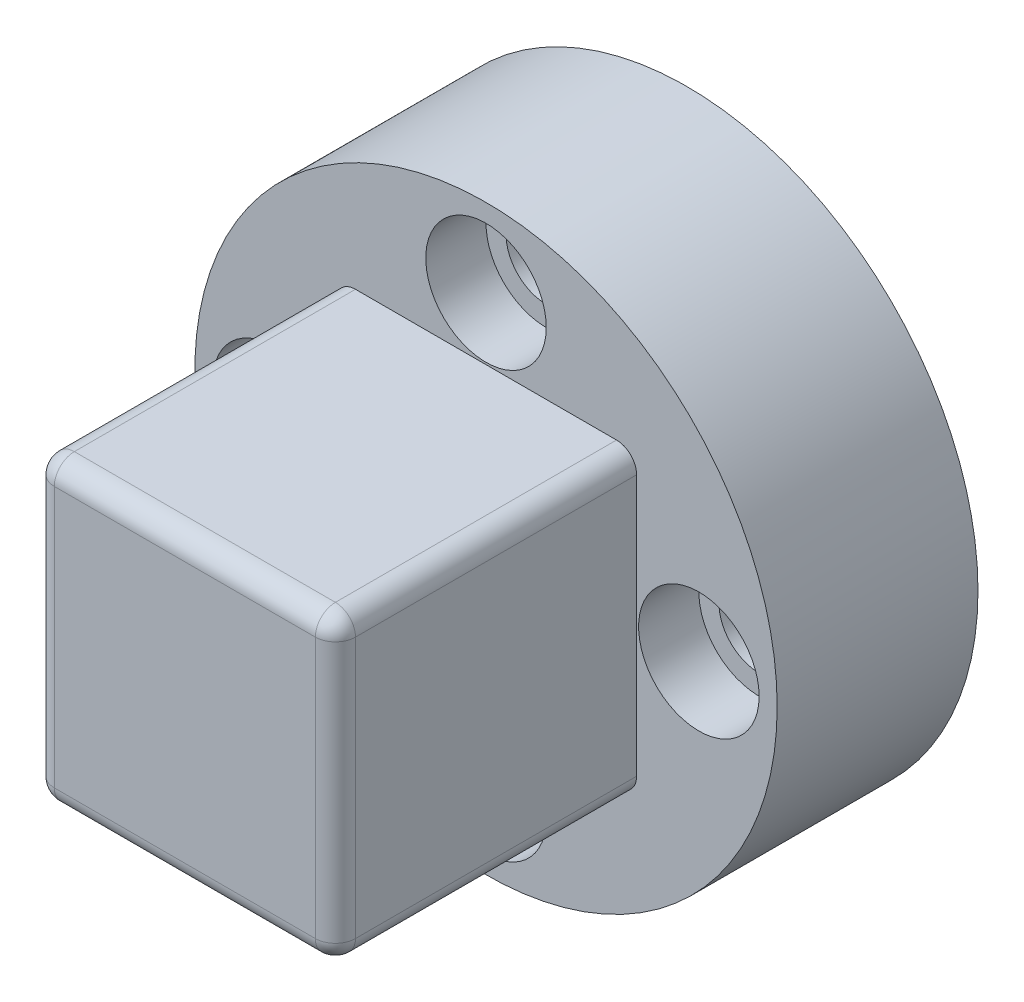
SolidWorks part; units mm, degrees
ref_plane "Front Plane" through (0, 0, 0) normal (0, 0, 1) x (1, 0, 0)
ref_plane "Top Plane" through (0, 0, 0) normal (0, 1, 0) x (1, 0, 0)
ref_plane "Right Plane" through (0, 0, 0) normal (1, 0, 0) x (0, 0, -1)
sketch "Sketch1" plane through (0, 0, 0) normal (0, 0, 1) x (1, 0, 0)
  circle A0 centre (0, 0) radius 14.5
  circle A1 centre (0, 0) radius 10.6
  circle A2 centre (10.6, 0) radius 2
  circle A3 centre (0, 10.6) radius 2
  circle A4 centre (-10.6, 0) radius 2
  circle A5 centre (0, -10.6) radius 2
  dimension "D1" = 29
  dimension "D2" = 21.2
  dimension "D3" = 4
extrude "Boss-Extrude3" add sketch "Sketch1" along normal blind 7 contours A0 | A2 | A5 | A3 | A4
sketch "Sketch3" plane through (0, 0, 7) normal (0, 0, 1) x (1, 0, 0)
  circle A0 centre (0, 0) radius 14.5 construction
  circle A1 centre (0, -10.6) radius 2 construction
  circle A2 centre (10.6, 0) radius 2 construction
  circle A3 centre (-10.6, 0) radius 2 construction
  circle A4 centre (0, 10.6) radius 2 construction
  circle A5 centre (0, 0) radius 14.5
  circle A6 centre (0, -10.6) radius 2
  circle A7 centre (10.6, 0) radius 2
  circle A8 centre (-10.6, 0) radius 2
  circle A9 centre (0, 10.6) radius 2
  circle A10 centre (0, 10.6) radius 3
  circle A11 centre (-10.6, 0) radius 3
  circle A12 centre (0, -10.6) radius 3
  circle A13 centre (10.6, 0) radius 3
  circle M10 centre (0, 0) radius 14.5
  dimension "D1" = 6
extrude "Boss-Extrude4" add sketch "Sketch3" along normal blind 3 contours A13 A12 A11 A10 M10
sketch "Sketch4" plane through (0, 0, 10) normal (0, 0, 1) x (1, 0, 0)
  line L1 (-7.5, -7.5) -> (7.5, -7.5)
  line L2 (-7.5, -7.5) -> (-7.5, 7.5)
  line L3 (-7.5, 7.5) -> (7.5, 7.5)
  line L4 (7.5, -7.5) -> (7.5, 7.5)
  line L5 (-7.5, -7.5) -> (7.5, 7.5) construction
  line L6 (-7.5, 7.5) -> (7.5, -7.5) construction
  point P0 (0, 0)
  dimension "D1" = 15
  dimension "15" = 15
extrude "Boss-Extrude5" add sketch "Sketch4" along normal blind 15
fillet "Fillet1" radius 1 8 edges at (0, 7.5, 25) (7.5, 0, 25) (0, -7.5, 25) (-7.5, 0, 25) (-7.5, 7.5, 17.5) (7.5, 7.5, 17.5) (7.5, -7.5, 17.5) (-7.5, -7.5, 17.5)
